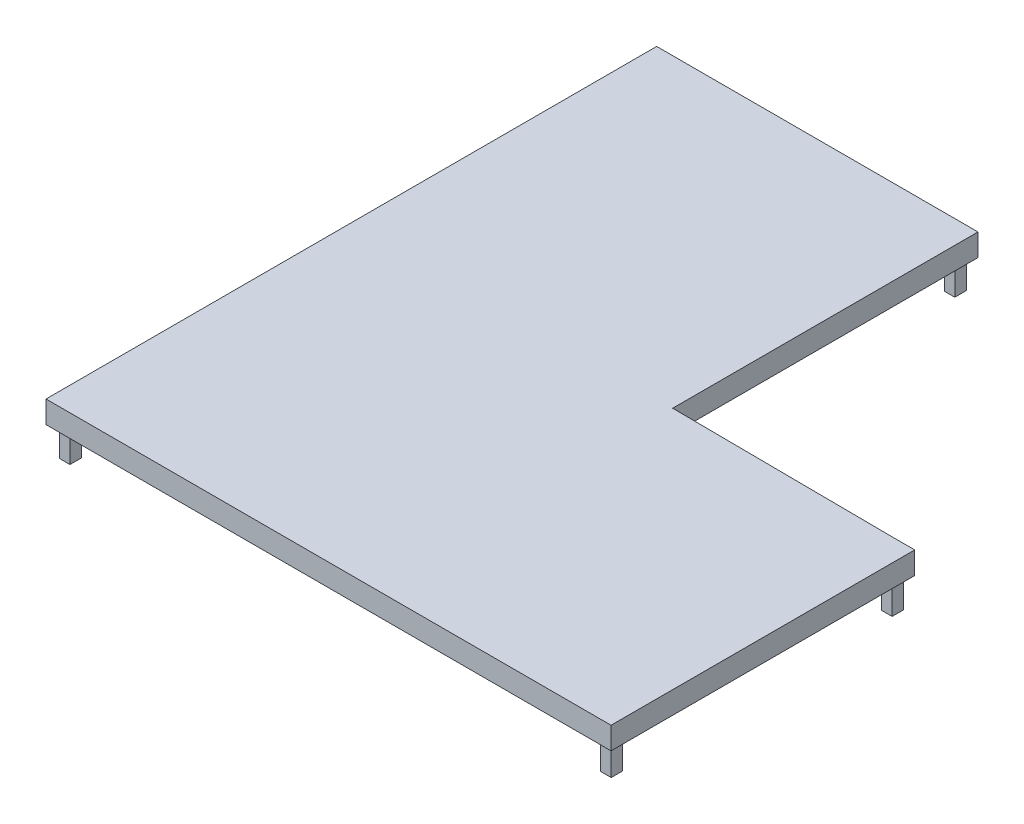
SolidWorks part; units mm, degrees
ref_plane "Front Plane" through (0, 0, 0) normal (0, 0, 1) x (1, 0, 0)
ref_plane "Top Plane" through (0, 0, 0) normal (0, 1, 0) x (1, 0, 0)
ref_plane "Right Plane" through (0, 0, 0) normal (1, 0, 0) x (0, 0, -1)
sketch "Sketch1" plane through (0, 0, 0) normal (0, 1, 0) x (1, 0, 0)
  line L11 (36.5271, -14.3266) -> (36.5271, -62.6095)
  line L12 (36.5271, -62.6095) -> (-60.4014, -62.6095)
  line L13 (-60.4014, -62.6095) -> (-60.4014, 42.1434)
  line L14 (-60.4014, 42.1434) -> (-9.0914, 42.1434)
  line L18 (36.5271, -10.5166) -> (32.7171, -10.5166)
  line L23 (-5.2814, 38.3334) -> (-5.2814, 42.1434)
  line L24 (-5.2814, 59.4834) -> (-5.2814, 38.3334) construction
  line L25 (-5.2814, 38.3334) -> (-5.2814, -58.7995) construction
  line L26 (32.7171, -10.5166) -> (-5.2814, -10.2331) construction
  line L27 (35.6628, -11.5817) -> (33.8565, -11.5817)
  line L28 (35.6628, -11.5817) -> (35.6628, -13.549)
  line L29 (35.6628, -13.549) -> (33.8565, -13.549)
  line L30 (33.8565, -11.5817) -> (33.8565, -13.549)
  line L31 (35.6628, -11.5817) -> (33.8565, -13.549) construction
  line L32 (35.6628, -13.549) -> (33.8565, -11.5817) construction
  line L33 (35.5057, -59.6113) -> (33.6994, -59.6113)
  line L34 (35.5057, -59.6113) -> (35.5057, -61.5785)
  line L35 (35.5057, -61.5785) -> (33.6994, -61.5785)
  line L36 (33.6994, -59.6113) -> (33.6994, -61.5785)
  line L37 (-6.3767, 41.2141) -> (-8.183, 41.2141)
  line L38 (-6.3767, 41.2141) -> (-6.3767, 39.2469)
  line L39 (-6.3767, 39.2469) -> (-8.183, 39.2469)
  line L40 (-8.183, 41.2141) -> (-8.183, 39.2469)
  line L41 (-57.6166, 40.9702) -> (-59.4229, 40.9702)
  line L42 (-57.6166, 40.9702) -> (-57.6166, 39.0029)
  line L43 (-57.6166, 39.0029) -> (-59.4229, 39.0029)
  line L44 (-59.4229, 40.9702) -> (-59.4229, 39.0029)
  line L45 (-57.4197, -59.5293) -> (-59.226, -59.5293)
  line L46 (-57.4197, -59.5293) -> (-57.4197, -61.4966)
  line L47 (-57.4197, -61.4966) -> (-59.226, -61.4966)
  line L48 (-59.226, -59.5293) -> (-59.226, -61.4966)
  line L49 (-5.2814, -10.2331) -> (32.7171, -10.5166)
  line L50 (-5.2814, -10.2331) -> (-5.2814, 38.3334)
  line L51 (36.5271, -14.3266) -> (36.5271, -10.5166)
  line L52 (-9.0914, 42.1434) -> (-5.2814, 42.1434)
  line L53 (36.5271, -10.5166) -> (36.5271, -14.4494)
extrude "Boss-Extrude1" add sketch "Sketch1" along normal blind 3.81 contours L18 L49 L50 L23 L52 L14 L13 L12 L11 L51
sketch "Sketch2" plane through (0, 3.81, 0) normal (0, 1, 0) x (1, 0, 0)
  line L0 (36.5389, -14.3214) -> (36.5389, -14.4441)
  line L4 (36.5389, -10.5114) -> (32.7289, -10.5114)
  line L6 (-5.2697, 38.3386) -> (-5.2697, -58.7942) construction
  line L7 (32.7289, -10.5114) -> (-5.2697, -10.2278) construction
  line L8 (35.6746, -11.5764) -> (33.8683, -11.5764)
  line L9 (35.6746, -11.5764) -> (35.6746, -13.5437)
  line L10 (35.6746, -13.5437) -> (33.8683, -13.5437)
  line L11 (33.8683, -11.5764) -> (33.8683, -13.5437)
  line L12 (35.6746, -11.5764) -> (33.8683, -13.5437) construction
  line L13 (35.6746, -13.5437) -> (33.8683, -11.5764) construction
  line L14 (35.5175, -59.606) -> (33.7112, -59.606)
  line L15 (35.5175, -59.606) -> (35.5175, -61.5733)
  line L16 (35.5175, -61.5733) -> (33.7112, -61.5733)
  line L17 (33.7112, -59.606) -> (33.7112, -61.5733)
  line L18 (-6.3649, 41.2194) -> (-8.1712, 41.2194)
  line L19 (-6.3649, 41.2194) -> (-6.3649, 39.2521)
  line L20 (-6.3649, 39.2521) -> (-8.1712, 39.2521)
  line L21 (-8.1712, 41.2194) -> (-8.1712, 39.2521)
  line L22 (-57.6049, 40.9754) -> (-59.4112, 40.9754)
  line L23 (-57.6049, 40.9754) -> (-57.6049, 39.0082)
  line L24 (-57.6049, 39.0082) -> (-59.4112, 39.0082)
  line L25 (-59.4112, 40.9754) -> (-59.4112, 39.0082)
  line L26 (-57.408, -59.524) -> (-59.2143, -59.524)
  line L27 (-57.408, -59.524) -> (-57.408, -61.4913)
  line L28 (-57.408, -61.4913) -> (-59.2143, -61.4913)
  line L29 (-59.2143, -59.524) -> (-59.2143, -61.4913)
  line L32 (36.5389, -14.3214) -> (36.5389, -10.5114)
  line L34 (36.5389, -10.5114) -> (36.5389, -14.4441)
extrude "Boss-Extrude3" add sketch "Sketch2" against normal blind 8.8 contours L8 L11 L10 L9 | L18 L21 L20 L19 | L22 L25 L24 L23 | L26 L29 L28 L27 | L14 L17 L16 L15
